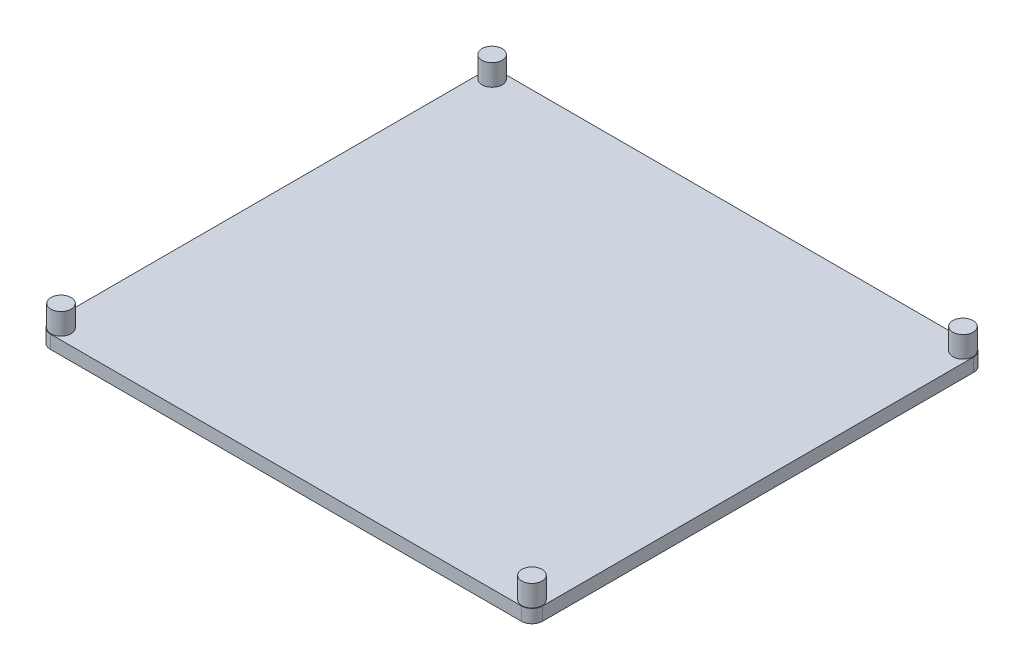
SolidWorks part; units mm, degrees
ref_plane "Front Plane" through (0, 0, 0) normal (0, 0, 1) x (1, 0, 0)
ref_plane "Top Plane" through (0, 0, 0) normal (0, 1, 0) x (1, 0, 0)
ref_plane "Right Plane" through (0, 0, 0) normal (1, 0, 0) x (0, 0, -1)
sketch "Sketch1" plane through (0, 0, 0) normal (0, 1, 0) x (1, 0, 0)
  line L0 (0, 0) -> (88.5, 0)
  line L1 (90.5, 2) -> (90.5, 83)
  line L2 (88.5, 85) -> (0, 85)
  line L3 (-2, 83) -> (-2, 2)
  arc A0 (88.5, 0) -> (90.5, 2) centre (88.5, 2) ccw
  arc A1 (90.5, 83) -> (88.5, 85) centre (88.5, 83) ccw
  arc A2 (0, 85) -> (-2, 83) centre (0, 83) ccw
  arc A3 (-2, 2) -> (0, 0) centre (0, 2) ccw
  dimension "D3" = 2
  dimension "D4" = 2
  dimension "D5" = 2
  dimension "D6" = 2
  dimension "D1" = 88.5
  dimension "D2" = 81
extrude "Boss-Extrude1" add sketch "Sketch1" along normal blind 2.5
sketch "Sketch3" plane through (0, 2.5, 0) normal (0, 1, 0) x (1, 0, 0)
  circle A0 centre (0, 83) radius 1.9
  circle A1 centre (88.5, 83) radius 1.9
  circle A2 centre (88.5, 2) radius 1.9
  circle A3 centre (0, 2) radius 1.9
  dimension "D1" = 3.8
  dimension "D2" = 3.8
  dimension "D3" = 3.8
  dimension "D4" = 3.8
  dimension "D5" = 88.5
  dimension "D6" = 81
  dimension "D7" = 88.5
  dimension "D8" = 81
extrude "Boss-Extrude2" add sketch "Sketch3" along normal blind 4
sketch "Sketch4" plane through (0, 0, 0) normal (0, -1, 0) x (1, 0, 0)
  line L0 (54.8143, -42.5344) -> (22.753, -42.5344) construction
  text T0 "BATTERY" font "Century Gothic" height 5
extrude "Cut-Extrude1" cut sketch "Sketch4" against normal blind 1.5
